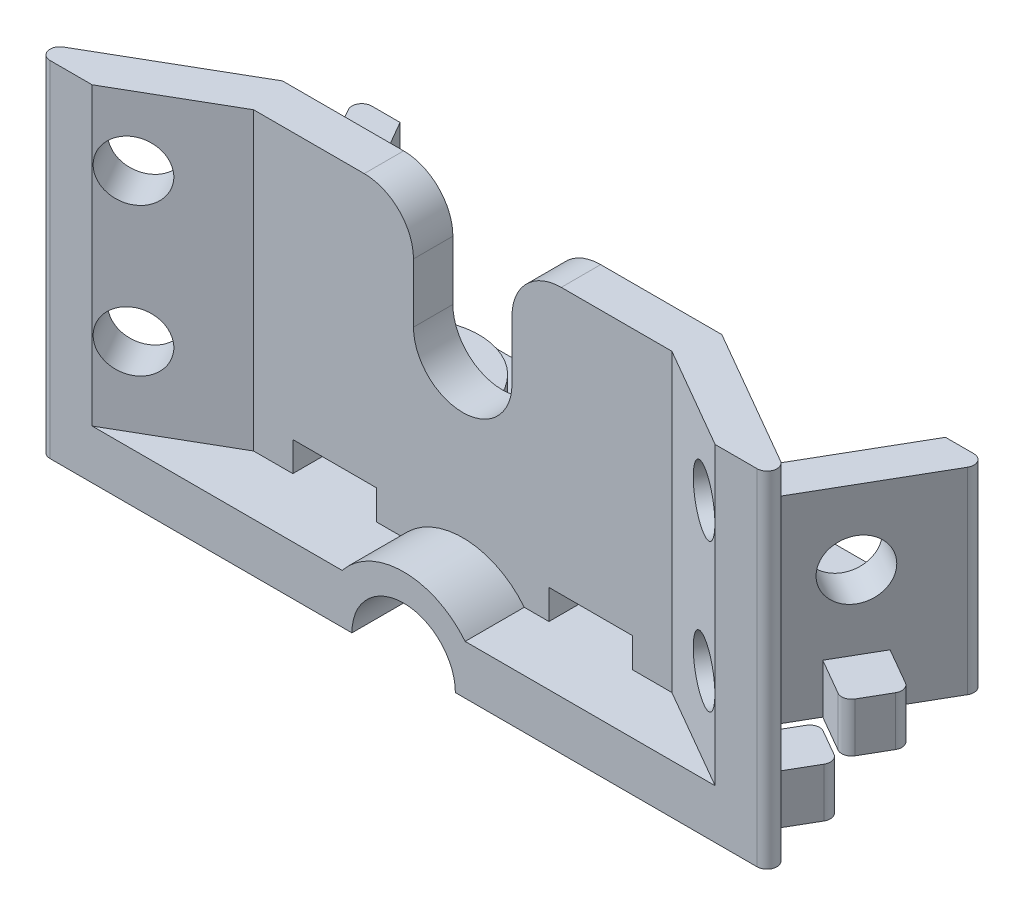
SolidWorks part; units mm, degrees
ref_plane "Front Plane" through (0, 0, 0) normal (0, 0, 1) x (1, 0, 0)
ref_plane "Top Plane" through (0, 0, 0) normal (0, 1, 0) x (1, 0, 0)
ref_plane "Right Plane" through (0, 0, 0) normal (1, 0, 0) x (0, 0, -1)
sketch "Sketch2" plane through (0, 0, 0) normal (0, 1, 0) x (1, 0, 0)
  line L0 (-30.5679, 27.3205) -> (30.5679, 27.3205)
  line L1 (0, 27.3205) -> (0, 0) construction
  line L2 (35.8885, 0) -> (-35.8885, 0)
  line L3 (-31.434, 25.8205) -> (-28.55, 20.8253)
  line L4 (-22.3, 10) -> (-28.7952, 6.25)
  line L5 (-33.1253, 3.75) -> (-36.3885, 1.866)
  line L6 (-28.55, 20.8253) -> (-32.2306, 18.7003)
  line L7 (-26.05, 16.4952) -> (-29.7306, 14.3702)
  line L8 (-32.5966, 17.3343) -> (-31.0966, 14.7362)
  line L9 (-28.55, 20.8253) -> (-26.05, 16.4952) construction
  line L10 (-33.1253, 3.75) -> (-35.2503, 7.4306)
  line L11 (-28.7952, 6.25) -> (-30.9202, 9.9306)
  line L12 (-34.8843, 8.7966) -> (-32.2862, 10.2966)
  line L13 (-26.05, 16.4952) -> (-22.3, 10)
  line L14 (-28.7952, 6.25) -> (-33.1253, 3.75) construction
  line L15 (28.7952, 6.25) -> (33.1253, 3.75) construction
  line L16 (28.55, 20.8253) -> (26.05, 16.4952) construction
  line L17 (26.05, 16.4952) -> (22.3, 10)
  line L18 (34.8843, 8.7966) -> (32.2862, 10.2966)
  line L19 (28.7952, 6.25) -> (30.9202, 9.9306)
  line L20 (33.1253, 3.75) -> (35.2503, 7.4306)
  line L21 (32.5966, 17.3343) -> (31.0966, 14.7362)
  line L22 (26.05, 16.4952) -> (29.7306, 14.3702)
  line L23 (28.55, 20.8253) -> (32.2306, 18.7003)
  line L24 (33.1253, 3.75) -> (36.3885, 1.866)
  line L25 (22.3, 10) -> (28.7952, 6.25)
  line L26 (31.434, 25.8205) -> (28.55, 20.8253)
  arc A0 (-32.2306, 18.7003) -> (-32.5966, 17.3343) centre (-31.7306, 17.8343) ccw
  arc A1 (-29.7306, 14.3702) -> (-31.0966, 14.7362) centre (-30.2306, 15.2362) cw
  arc A2 (-30.9202, 9.9306) -> (-32.2862, 10.2966) centre (-31.7862, 9.4306) ccw
  arc A3 (-35.2503, 7.4306) -> (-34.8843, 8.7966) centre (-34.3843, 7.9306) cw
  arc A4 (-30.5679, 27.3205) -> (-31.434, 25.8205) centre (-30.5679, 26.3205) ccw
  arc A5 (-35.8885, 0) -> (-36.3885, 1.866) centre (-35.8885, 1) cw
  arc A6 (35.8885, 0) -> (36.3885, 1.866) centre (35.8885, 1) ccw
  arc A7 (30.5679, 27.3205) -> (31.434, 25.8205) centre (30.5679, 26.3205) cw
  arc A8 (35.2503, 7.4306) -> (34.8843, 8.7966) centre (34.3843, 7.9306) ccw
  arc A9 (30.9202, 9.9306) -> (32.2862, 10.2966) centre (31.7862, 9.4306) cw
  arc A10 (29.7306, 14.3702) -> (31.0966, 14.7362) centre (30.2306, 15.2362) ccw
  arc A11 (32.2306, 18.7003) -> (32.5966, 17.3343) centre (31.7306, 17.8343) cw
  point P7 (-33.5853, 9.5466)
  point P18 (-32.3, 27.3205)
  point P21 (-39.6205, 0)
  point P30 (-33.0966, 18.2003)
  point P33 (-30.5966, 13.8702)
  point P36 (-31.4202, 10.7966)
  point P39 (-35.7503, 8.2966)
  point P57 (35.7503, 8.2966)
  point P58 (31.4202, 10.7966)
  point P59 (30.5966, 13.8702)
  point P60 (33.0966, 18.2003)
  point P61 (39.6205, 0)
  point P62 (32.3, 27.3205)
  dimension "D8" = 1
  dimension "D9" = 1
  dimension "D10" = 1
  dimension "D1" = 5
  dimension "D2" = 20
  dimension "D3" = 10
  dimension "D4" = 5.25
  dimension "D5" = 30
  dimension "D6" = 20
  dimension "D7" = 32.3
extrude "Boss-Extrude1" add sketch "Sketch2" along normal blind 5
sketch "Sketch3" plane through (0, 5, 0) normal (0, 1, 0) x (1, 0, 0)
  line L0 (-36.3885, 1.866) -> (-22.3, 10)
  line L1 (-22.3, 10) -> (22.3, 10)
  line L2 (22.3, 10) -> (36.3885, 1.866)
  line L3 (-35.8885, 0) -> (-31.6205, 0)
  line L4 (-35.8885, 0) -> (35.8885, 0) construction
  line L5 (-31.6205, 0) -> (-21.2282, 6)
  line L6 (-21.2282, 6) -> (21.2282, 6)
  line L7 (21.2282, 6) -> (31.6205, 0)
  line L8 (31.6205, 0) -> (35.8885, 0)
  arc A0 (35.8885, 0) -> (36.3885, 1.866) centre (35.8885, 1) ccw construction
  arc A1 (-36.3885, 1.866) -> (-35.8885, 0) centre (-35.8885, 1) ccw construction
  arc A2 (35.8885, 0) -> (36.3885, 1.866) centre (35.8885, 1) ccw
  arc A3 (-36.3885, 1.866) -> (-35.8885, 0) centre (-35.8885, 1) ccw
  dimension "D1" = 4
  dimension "D2" = 4
  dimension "D3" = 4
extrude "Boss-Extrude2" add sketch "Sketch3" along normal blind 30
sketch "Sketch4" plane through (0, 5, 0) normal (0, 1, 0) x (1, 0, 0)
  line L0 (22.3, 10) -> (31.434, 25.8205)
  line L1 (22.3, 10) -> (17.6812, 10)
  line L2 (22.3, 10) -> (-22.3, 10) construction
  line L3 (17.6812, 10) -> (27.6812, 27.3205)
  line L4 (30.5679, 27.3205) -> (-30.5679, 27.3205) construction
  line L5 (27.6812, 27.3205) -> (30.5679, 27.3205)
  line L6 (0, 10) -> (0, 27.3205) construction
  line L7 (-27.6812, 27.3205) -> (-30.5679, 27.3205)
  line L8 (-17.6812, 10) -> (-27.6812, 27.3205)
  line L9 (-22.3, 10) -> (-17.6812, 10)
  line L10 (-22.3, 10) -> (-31.434, 25.8205)
  arc A0 (31.434, 25.8205) -> (30.5679, 27.3205) centre (30.5679, 26.3205) ccw construction
  arc A1 (31.434, 25.8205) -> (30.5679, 27.3205) centre (30.5679, 26.3205) ccw
  arc A2 (-31.434, 25.8205) -> (-30.5679, 27.3205) centre (-30.5679, 26.3205) cw
  dimension "D1" = 4
extrude "Boss-Extrude3" add sketch "Sketch4" along normal blind 15
sketch "Sketch5" plane through (0, 0, 0) normal (0, 0, 1) x (1, 0, 0)
  line L0 (-35.8885, 0) -> (35.8885, 0) construction
  line L1 (-8, 0) -> (8, 0)
  arc A0 (8, 0) -> (-8, 0) centre (0, 0) ccw
  dimension "D1" = 16
extrude "Boss-Extrude4" add sketch "Sketch5" against normal up to surface (27.3205 mm away)
sketch "Sketch6" plane through (0, 0, 0) normal (0, 0, 1) x (1, 0, 0)
  circle A0 centre (0, 0) radius 5.25
  dimension "D1" = 10.5
extrude "Cut-Extrude1" cut sketch "Sketch6" against normal through all
sketch "Sketch7" plane through (0, 0, -6) normal (0, 0, 1) x (1, 0, 0)
  line L0 (-10, 35) -> (10, 35)
  line L1 (-21.2282, 35) -> (21.2282, 35) construction
  line L2 (-5, 30) -> (-5, 24)
  line L3 (0, 35) -> (0, 19) construction
  line L4 (5, 30) -> (5, 24)
  arc A0 (-10, 35) -> (-5, 30) centre (-10, 30) cw
  arc A1 (-5, 24) -> (5, 24) centre (0, 24) ccw
  arc A2 (10, 35) -> (5, 30) centre (10, 30) ccw
  dimension "D3" = 5
  dimension "D1" = 5
  dimension "D2" = 6
extrude "Cut-Extrude2" cut sketch "Sketch7" against normal through all
sketch "Sketch8" plane through (-9.9051, 0, -17.1562) normal (-0.5, 0, -0.866) x (-0.866, 0, 0.5)
  line L0 (26.8124, 5) -> (21.8124, 5) construction
  circle A0 centre (24.3124, 28) radius 3
  circle A1 centre (24.3124, 13) radius 3
  point P6 (24.3124, 5)
  dimension "D3" = 6
  dimension "D1" = 8
  dimension "D2" = 15
extrude "Cut-Extrude3" cut sketch "Sketch8" against normal through all
sketch "Sketch9" plane through (-12.3949, 0, 7.1562) normal (-0.866, 0, 0.5) x (0.5, 0, 0.866)
  line L0 (-32.3103, 5) -> (-27.3103, 5) construction
  line L2 (-29.8103, 20) -> (-29.8103, 5) construction
  line L3 (-38.0782, 20) -> (-19.8103, 20) construction
  circle A0 centre (-29.8103, 12.5) radius 3
  point P2 (-29.8103, 5)
  point P9 (-29.8103, 12.5)
  dimension "D1" = 6
extrude "Cut-Extrude4" cut sketch "Sketch9" against normal through all
sketch "Sketch10" plane through (0, 5, 0) normal (0, 1, 0) x (1, 0, 0)
  line L0 (0, 27.3205) -> (0, 0) construction
  line L1 (6.245, 27.3205) -> (-6.245, 27.3205) construction
  circle A0 centre (-13, 13.6603) radius 7
  point P7 (0, 13.6603)
  dimension "D2" = 14
  dimension "D1" = 13
extrude "Boss-Extrude5" add sketch "Sketch10" along normal blind 7
sketch "Sketch11" plane through (0, 12, 0) normal (0, 1, 0) x (1, 0, 0)
  circle A0 centre (-13, 13.6603) radius 3
  arc A1 (-7.0332, 10) -> (-19.9917, 14.0018) centre (-13, 13.6603) ccw construction
  dimension "D1" = 6
extrude "Cut-Extrude5" cut sketch "Sketch11" against normal through all
sketch "Sketch13" plane through (0, 5, 0) normal (0, 1, 0) x (1, 0, 0)
  line L0 (-17.25, 11.2065) -> (-17.25, 6)
  line L1 (-13, 8.7528) -> (-8.75, 11.2065) construction
  line L2 (-8.75, 11.2065) -> (-8.75, 16.114)
  line L3 (-8.75, 16.114) -> (-13, 18.5677)
  line L4 (-13, 18.5677) -> (-17.25, 16.114)
  line L5 (-17.25, 16.114) -> (-17.25, 11.2065)
  line L6 (-17.25, 11.2065) -> (-13, 8.7528) construction
  line L7 (-21.2282, 6) -> (-6.245, 6) construction
  line L8 (-17.25, 6) -> (-8.75, 6)
  line L9 (-8.75, 6) -> (-8.75, 11.2065)
  circle A0 centre (-13, 13.6603) radius 4.25 construction
  circle A1 centre (-13, 13.6603) radius 3 construction
  dimension "D1" = 8.5
extrude "Cut-Extrude6" cut sketch "Sketch13" along normal blind 3
sketch "Sketch14" plane through (0, 0, -6) normal (0, 0, 1) x (1, 0, 0)
  line L2 (-17.25, 8) -> (-8.75, 8) construction
  line L3 (-8.75, 8) -> (-8.75, 5) construction
  circle A0 centre (-13, 6.5) radius 1.5
  point P4 (-13, 8)
  point P7 (-8.75, 6.5)
extrude "Cut-Extrude7" cut sketch "Sketch14" against normal through all
mirror "Mirror1" about plane through (0, 0, 0) normal (1, 0, 0) of "Cut-Extrude3", "Cut-Extrude4", "Boss-Extrude5", "Cut-Extrude5", "Cut-Extrude6", "Cut-Extrude7"
